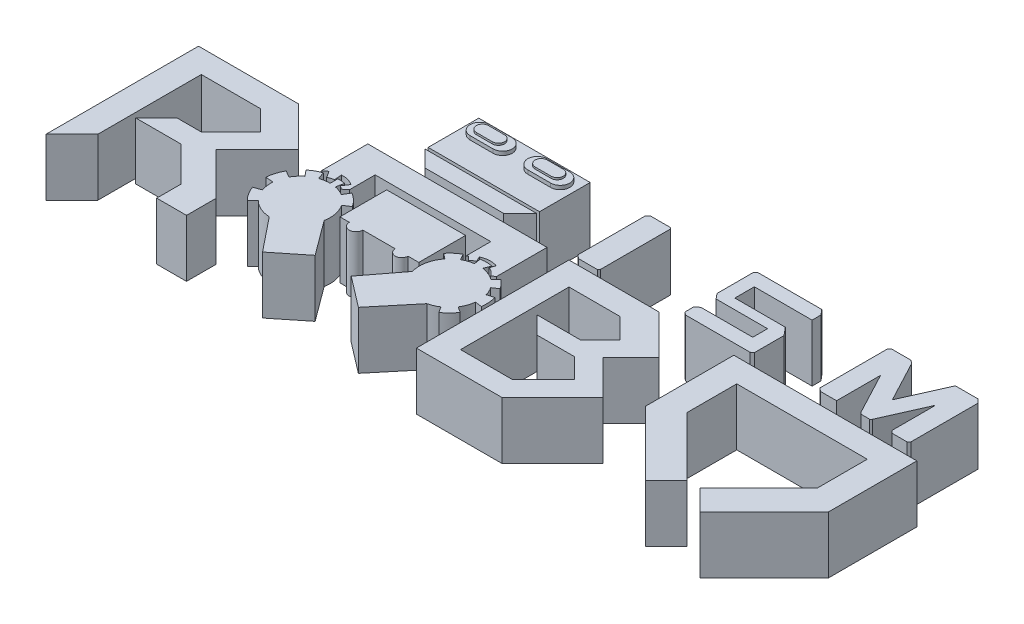
SolidWorks part; units mm, degrees
ref_plane "Front Plane" through (0, 0, 0) normal (0, 0, 1) x (1, 0, 0)
ref_plane "Top Plane" through (0, 0, 0) normal (0, 1, 0) x (1, 0, 0)
ref_plane "Right Plane" through (0, 0, 0) normal (1, 0, 0) x (0, 0, -1)
sketch "Sketch1" plane through (0, 0, 0) normal (0, 1, 0) x (1, 0, 0)
  line L0 (-166.0607, 37.3597) -> (-166.0607, -2.6403)
  line L1 (-166.0607, 37.3597) -> (-139.8845, 37.3597)
  line L2 (-139.8845, 37.3597) -> (-129.4521, 26.9273)
  line L3 (-129.4521, 26.9273) -> (-140.2451, 16.1343)
  line L4 (-140.2451, 16.1343) -> (-129.2099, 5.0991)
  line L5 (-129.2099, 5.0991) -> (-129.2099, -2.6403)
  line L6 (-129.2099, -2.6403) -> (-137.028, -2.6403)
  line L7 (-137.028, -2.6403) -> (-137.028, 3.7846)
  line L8 (-137.028, 3.7846) -> (-146.0682, 12.8249)
  line L9 (-146.0682, 12.8249) -> (-158.0341, 12.8249)
  line L10 (-158.0341, 12.8249) -> (-152.6239, 18.235)
  line L11 (-152.6239, 18.235) -> (-146.1008, 18.235)
  line L12 (-146.1008, 18.235) -> (-138.4117, 25.9241)
  line L13 (-138.4117, 25.9241) -> (-143.7761, 31.2885)
  line L14 (-143.7761, 31.2885) -> (-159.2623, 31.2885)
  line L15 (-166.0607, -2.6403) -> (-159.2623, 4.1581)
  line L16 (-159.2623, 4.1581) -> (-159.2623, 31.2885)
  line L17 (-121.667, 37.3597) -> (-121.667, 25.0918)
  line L20 (-113.667, 24.5458) -> (-113.667, 31.2885)
  line L21 (-113.667, 31.2885) -> (-83.3506, 31.2885)
  line L23 (-83.3506, 31.2885) -> (-83.3506, 24.6864)
  line L25 (-74.667, 24.0883) -> (-74.667, 37.3597)
  line L26 (-74.667, 37.3597) -> (-121.667, 37.3597)
  line L27 (-108.7566, 29.3969) -> (-88.0688, 29.3969)
  line L28 (-88.0688, 29.3969) -> (-88.0688, 17.1359)
  line L29 (-88.0688, 17.1359) -> (-90.8996, 17.1359)
  line L30 (-108.7566, 17.1359) -> (-108.7566, 29.3969)
  line L31 (-68.9283, 37.3597) -> (-68.9283, -2.6403)
  line L32 (-68.9283, -2.6403) -> (-63.4351, -2.6403)
  line L36 (-34.9709, 27.0743) -> (-45.2564, 37.3597)
  line L37 (-45.2564, 37.3597) -> (-68.9283, 37.3597)
  line L38 (-62.7878, 31.2387) -> (-62.7878, 2.8008)
  line L39 (-62.7878, 2.8008) -> (-49.1858, 2.8008)
  line L40 (-49.1858, 2.8008) -> (-41.072, 10.9146)
  line L41 (-41.072, 10.9146) -> (-46.2918, 16.1343)
  line L42 (-46.2918, 16.1343) -> (-56.1233, 16.1343)
  line L43 (-56.1233, 16.1343) -> (-60.7089, 20.7199)
  line L44 (-60.7089, 20.7199) -> (-49.337, 20.7199)
  line L45 (-49.337, 20.7199) -> (-44.1327, 25.9241)
  line L46 (-44.1327, 25.9241) -> (-49.4473, 31.2387)
  line L47 (-49.4473, 31.2387) -> (-62.7878, 31.2387)
  line L48 (-25.6765, 37.3597) -> (-25.6765, 14.2331)
  line L49 (-25.6765, 14.2331) -> (-8.8031, -2.6403)
  line L50 (-8.8031, -2.6403) -> (-3.3621, 2.8008)
  line L51 (-3.3621, 2.8008) -> (-18.7963, 18.235)
  line L52 (-18.7963, 18.235) -> (-18.7963, 31.2387)
  line L53 (0, 2.8008) -> (5.4411, -2.6403)
  line L54 (5.4411, -2.6403) -> (22.3145, 14.2331)
  line L55 (22.3145, 14.2331) -> (22.3145, 37.3597)
  line L56 (22.3145, 37.3597) -> (-25.6765, 37.3597)
  line L57 (0, 2.8008) -> (15.4342, 18.235)
  line L58 (15.4342, 18.235) -> (15.4342, 31.2387)
  line L59 (15.4342, 31.2387) -> (-18.7963, 31.2387)
  line L60 (-108.7566, 39.392) -> (-88.0688, 39.392)
  line L61 (-88.0688, 39.392) -> (-83.7572, 43.7037)
  line L62 (-108.7566, 39.392) -> (-113.0683, 43.7037)
  line L63 (-113.0683, 43.7037) -> (-83.7572, 43.7037)
  line L64 (-83.7503, 44.4766) -> (-112.9679, 44.4766)
  line L65 (-112.9679, 44.4766) -> (-112.9679, 57.7563)
  line L66 (-112.9679, 57.7563) -> (-83.7503, 57.7563)
  line L67 (-83.7503, 57.7563) -> (-83.7503, 44.4766)
  line L80 (-68.9283, 57.4217) -> (-68.9283, 39.6857)
  line L81 (-67.9599, 38.9277) -> (-63.0123, 38.9277)
  line L82 (-62.6576, 39.381) -> (-62.6576, 57.716)
  line L83 (-62.9941, 58.0525) -> (-68.2975, 58.0525)
  line L84 (-6.9618, 58.9988) -> (-6.9618, 41.2018)
  line L85 (-6.0797, 40.4957) -> (-1.8753, 40.4957)
  line L86 (-1.8753, 40.4957) -> (-1.8753, 52.0468)
  line L87 (-1.8753, 52.0468) -> (3.9673, 41.0241)
  line L88 (4.45, 40.6377) -> (6.6837, 40.6377)
  line L89 (7.0668, 41.0207) -> (12.135, 52.4627)
  line L90 (12.135, 52.4627) -> (12.135, 40.9578)
  line L91 (12.7035, 40.3893) -> (16.7401, 40.3893)
  line L92 (17.2222, 40.8713) -> (17.2222, 58.4882)
  line L93 (16.2517, 59.4587) -> (10.3092, 59.4587)
  line L94 (10.3092, 59.4587) -> (5.238, 48.0101)
  line L95 (5.238, 48.0101) -> (-0.496, 58.8278)
  line L96 (-1.3264, 59.4587) -> (-6.5019, 59.4587)
  line L97 (-41.9161, 58.7009) -> (-41.9161, 49.1769)
  line L98 (-40.7713, 47.8082) -> (-27.2826, 47.8082)
  line L99 (-27.2826, 47.8082) -> (-27.2826, 43.9183)
  line L100 (-27.2826, 43.9183) -> (-40.8784, 43.9183)
  line L101 (-41.9161, 43.0505) -> (-41.9161, 40.7584)
  line L102 (-41.1244, 40.1642) -> (-24.2273, 40.1642)
  line L103 (-23.5737, 40.7108) -> (-23.5737, 48.4215)
  line L104 (-25.2927, 50.4768) -> (-38.5334, 50.4768)
  line L105 (-38.5334, 50.4768) -> (-38.5334, 55.5935)
  line L106 (-38.5334, 55.5935) -> (-23.3964, 55.5935)
  line L107 (-23.3964, 55.5935) -> (-23.3964, 57.9202)
  line L108 (-24.5467, 59.289) -> (-41.2163, 59.289)
  line L109 (-6.9618, 58.9988) -> (-6.5019, 59.4587)
  line L110 (-1.3264, 59.4587) -> (-0.496, 58.8278)
  line L111 (-34.9709, 27.0743) -> (-42.3552, 19.69)
  line L112 (-42.3552, 19.69) -> (-33.2674, 10.6023)
  line L113 (-33.2674, 10.6023) -> (-46.51, -2.6403)
  line L114 (-46.51, -2.6403) -> (-63.4351, -2.6403)
  line L115 (-68.9283, 57.4217) -> (-68.2975, 58.0525)
  line L116 (-62.9941, 58.0525) -> (-62.6576, 57.716)
  line L117 (-63.0123, 38.9277) -> (-62.6576, 39.381)
  line L118 (-68.9283, 39.6857) -> (-67.9599, 38.9277)
  line L119 (-41.9161, 58.7009) -> (-41.2163, 59.289)
  line L120 (-24.5467, 59.289) -> (-23.3964, 57.9202)
  line L121 (-41.9161, 49.1769) -> (-40.7713, 47.8082)
  line L122 (-25.2927, 50.4768) -> (-23.5737, 48.4215)
  line L123 (-24.2273, 40.1642) -> (-23.5737, 40.7108)
  line L124 (-41.9161, 43.0505) -> (-40.8784, 43.9183)
  line L125 (-41.9161, 40.7584) -> (-41.1244, 40.1642)
  line L126 (-119.4658, 24.3434) -> (-120.5039, 26.0446)
  line L127 (16.2517, 59.4587) -> (17.2222, 58.4882)
  line L128 (16.7401, 40.3893) -> (17.2222, 40.8713)
  line L129 (12.135, 40.9578) -> (12.7035, 40.3893)
  line L130 (6.6837, 40.6377) -> (7.0668, 41.0207)
  line L131 (4.45, 40.6377) -> (3.9673, 41.0241)
  line L132 (-6.9618, 41.2018) -> (-6.0797, 40.4957)
  line L133 (-117.9053, 24.8407) -> (-118.0429, 26.8289)
  line L134 (-115.7485, 24.267) -> (-114.6413, 25.9241)
  line L135 (-114.9539, 23.5322) -> (-113.667, 24.5458)
  line L136 (-81.9441, 24.1064) -> (-83.0111, 25.0918)
  line L137 (-80.7464, 24.9936) -> (-81.378, 26.3015)
  line L138 (-77.6384, 25.1488) -> (-77.1403, 26.5132)
  line L139 (-75.6132, 23.5015) -> (-74.667, 24.0883)
  line L140 (-106.2995, 17.1359) -> (-108.7566, 17.1359)
  line L141 (-94.2412, 17.1359) -> (-102.7253, 17.1359)
  line L143 (-110.916, -0.9935) -> (-103.2671, 5.1454)
  line L144 (-86.8577, 14.2331) -> (-93.8103, 5.1454)
  line L145 (-93.8103, 5.1454) -> (-85.7862, -0.9935)
  line L146 (-118.0429, 7.8864) -> (-110.916, -0.9935)
  line L147 (-109.9971, 14.2331) -> (-103.2671, 5.1454)
  line L148 (-85.7862, -0.9935) -> (-77.6384, 8.8213)
  line L149 (-80.7464, 25.9479) -> (-80.4871, 24.158)
  line L150 (-77.6384, 25.8902) -> (-78.3376, 24.1703)
  line L151 (-74.667, 22.6639) -> (-73.378, 23.9529)
  line L152 (-72.9109, 20.8181) -> (-71.4147, 21.8341)
  line L153 (-83.2244, 23.2197) -> (-84.1178, 24.7922)
  line L154 (-85.4489, 21.3275) -> (-86.8577, 22.4615)
  line L155 (-116.1452, 23.339) -> (-115.7485, 25.335)
  line L156 (-117.667, 23.4887) -> (-117.667, 25.5238)
  line L157 (-71.8769, 18.6255) -> (-70.1412, 19.1335)
  line L158 (-71.6152, 15.529) -> (-69.8188, 15.3195)
  line L159 (-72.8158, 12.1911) -> (-71.2977, 11.2083)
  line L160 (-75.0642, 9.9211) -> (-74.067, 8.4124)
  line L161 (-120.2582, 23.0461) -> (-120.9338, 24.9657)
  line L162 (-122.5688, 21.7576) -> (-123.8468, 23.3414)
  line L163 (-124.4696, 19.511) -> (-126.2431, 20.509)
  line L164 (-125.45, 16.2778) -> (-127.4791, 16.4329)
  line L165 (-125.0302, 13.0925) -> (-126.95, 12.417)
  line L166 (-123.1864, 10.1636) -> (-124.6254, 8.7246)
  line L167 (-113.6401, 22.3699) -> (-112.5902, 24.1132)
  line L168 (-111.1489, 19.9776) -> (-109.4495, 21.0973)
  arc A0 (-121.667, 25.0918) -> (-120.5039, 26.0446) centre (-117.667, 21.3955) cw
  arc A1 (-83.3506, 24.6864) -> (-83.0111, 25.0918) centre (-79.0088, 21.3955) cw
  arc A2 (-75.6132, 23.5015) -> (-77.6384, 25.1488) centre (-79.0088, 21.3955) ccw
  arc A3 (-114.9539, 23.5322) -> (-115.7485, 24.267) centre (-117.667, 21.3955) ccw
  arc A4 (-118.0429, 26.8289) -> (-114.6413, 25.9241) centre (-117.667, 21.3955) cw
  arc A5 (-117.9053, 24.8407) -> (-119.4658, 24.3434) centre (-117.667, 21.3955) ccw
  arc A6 (-80.7464, 24.9936) -> (-81.9441, 24.1064) centre (-79.0088, 21.3955) ccw
  arc A7 (-81.378, 26.3015) -> (-77.1403, 26.5132) centre (-79.0088, 21.3955) cw
  arc A8 (-106.2995, 17.1359) -> (-102.7253, 17.1359) centre (-104.5124, 17.1359) ccw
  arc A9 (-94.2412, 17.1359) -> (-90.8996, 17.1359) centre (-92.5704, 17.1359) ccw
  arc A10 (-109.9971, 14.2331) -> (-111.1489, 19.9776) centre (-117.667, 15.683) ccw
  arc A11 (-77.6384, 8.8213) -> (-75.0642, 9.9211) centre (-79.3684, 16.4329) ccw
  arc A12 (-86.8577, 22.4615) -> (-84.1178, 24.7922) centre (-79.3684, 16.4329) cw
  arc A13 (-80.4871, 24.158) -> (-83.2244, 23.2197) centre (-79.3684, 16.4329) ccw
  arc A14 (-80.7464, 25.9479) -> (-77.6384, 25.8902) centre (-79.3684, 16.4329) cw
  arc A15 (-85.4489, 21.3275) -> (-86.8577, 14.2331) centre (-79.3684, 16.4329) ccw
  arc A16 (-73.378, 23.9529) -> (-71.4147, 21.8341) centre (-79.3684, 16.4329) cw
  arc A17 (-74.667, 22.6639) -> (-78.3376, 24.1703) centre (-79.3684, 16.4329) ccw
  arc A18 (-70.1412, 19.1335) -> (-69.8188, 15.3195) centre (-79.3684, 16.4329) cw
  arc A19 (-71.8769, 18.6255) -> (-72.9109, 20.8181) centre (-79.3684, 16.4329) ccw
  arc A20 (-71.2977, 11.2083) -> (-74.067, 8.4124) centre (-79.3684, 16.4329) cw
  arc A21 (-72.8158, 12.1911) -> (-71.6152, 15.529) centre (-79.3684, 16.4329) ccw
  arc A22 (-120.9338, 24.9657) -> (-123.8468, 23.3414) centre (-117.667, 15.683) ccw
  arc A23 (-117.667, 23.4887) -> (-120.2582, 23.0461) centre (-117.667, 15.683) ccw
  arc A24 (-126.2431, 20.509) -> (-127.4791, 16.4329) centre (-117.667, 15.683) ccw
  arc A25 (-126.95, 12.417) -> (-124.6254, 8.7246) centre (-117.667, 15.683) ccw
  arc A26 (-109.4495, 21.0973) -> (-112.5902, 24.1132) centre (-117.667, 15.683) ccw
  arc A27 (-122.5688, 21.7576) -> (-124.4696, 19.511) centre (-117.667, 15.683) ccw
  arc A28 (-125.45, 16.2778) -> (-125.0302, 13.0925) centre (-117.667, 15.683) ccw
  arc A30 (-115.7485, 25.335) -> (-117.667, 25.5238) centre (-117.667, 15.683) ccw
  arc A31 (-113.6401, 22.3699) -> (-116.1452, 23.339) centre (-117.667, 15.683) ccw
  arc A32 (-123.1864, 10.1636) -> (-118.0429, 7.8864) centre (-117.667, 15.683) ccw
extrude "Boss-Extrude1" add sketch "Sketch1" along normal blind 15
sketch "Sketch2" plane through (0, 15, 0) normal (0, 1, 0) x (1, 0, 0)
  line L0 (-109.1187, 54.1664) -> (-103.1187, 54.1664) construction
  line L1 (-109.1187, 56.6842) -> (-103.1187, 56.6842)
  line L2 (-109.1187, 51.6485) -> (-103.1187, 51.6485)
  line L3 (-93.8046, 53.9594) -> (-87.8046, 53.9594) construction
  line L4 (-93.8046, 56.4773) -> (-87.8046, 56.4773)
  line L5 (-93.8046, 51.4416) -> (-87.8046, 51.4416)
  arc A0 (-109.1187, 56.6842) -> (-109.1187, 51.6485) centre (-109.1187, 54.1664) ccw
  arc A1 (-103.1187, 51.6485) -> (-103.1187, 56.6842) centre (-103.1187, 54.1664) ccw
  arc A2 (-93.8046, 56.4773) -> (-93.8046, 51.4416) centre (-93.8046, 53.9594) ccw
  arc A3 (-87.8046, 51.4416) -> (-87.8046, 56.4773) centre (-87.8046, 53.9594) ccw
  point P2 (-106.1187, 54.1664)
  point P9 (-90.8046, 53.9594)
  point P14 (0, 0)
  point P15 (0, 0)
extrude "Boss-Extrude2" add sketch "Sketch2" along normal blind 1
sketch "Sketch3" plane through (0, 16, 0) normal (0, 1, 0) x (1, 0, 0)
  line L0 (-108.5129, 54.2665) -> (-104.3129, 54.2665) construction
  line L1 (-108.5129, 55.8531) -> (-104.3129, 55.8531)
  line L2 (-108.5129, 52.6799) -> (-104.3129, 52.6799)
  line L3 (-92.9837, 54.149) -> (-88.7837, 54.149) construction
  line L4 (-92.9837, 55.7356) -> (-88.7837, 55.7356)
  line L5 (-92.9837, 52.5624) -> (-88.7837, 52.5624)
  arc A0 (-108.5129, 55.8531) -> (-108.5129, 52.6799) centre (-108.5129, 54.2665) ccw
  arc A1 (-104.3129, 52.6799) -> (-104.3129, 55.8531) centre (-104.3129, 54.2665) ccw
  arc A2 (-92.9837, 55.7356) -> (-92.9837, 52.5624) centre (-92.9837, 54.149) ccw
  arc A3 (-88.7837, 52.5624) -> (-88.7837, 55.7356) centre (-88.7837, 54.149) ccw
  point P2 (-106.4129, 54.2665)
  point P7 (0, 0)
  point P8 (0, 0)
  point P11 (-90.8837, 54.149)
extrude "Boss-Extrude3" add sketch "Sketch3" along normal blind 0.5
sketch "Sketch4" plane through (0, 15, 0) normal (0, 1, 0) x (1, 0, 0)
  circle A0 centre (-117.9627, 16.4123) radius 3
  circle A1 centre (-117.9627, 16.4123) radius 2
  circle A2 centre (-79.7361, 16.3302) radius 3
  circle A3 centre (-79.7361, 16.3302) radius 2
  point P6 (0, 0)
